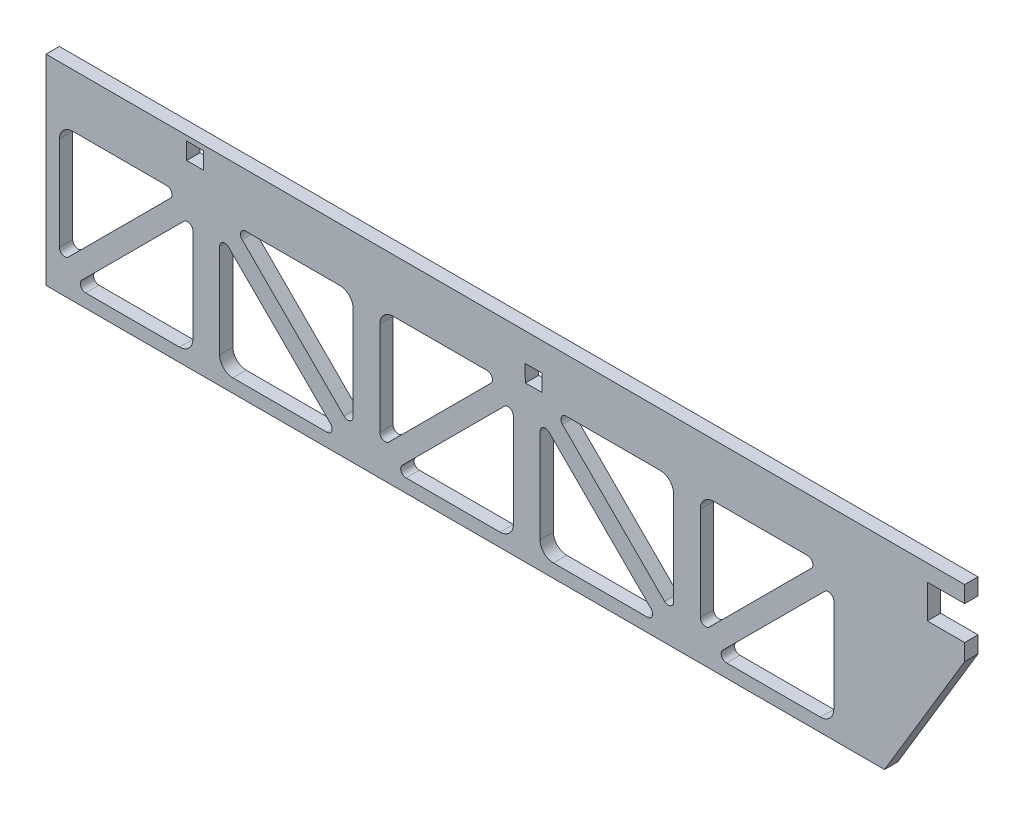
SolidWorks part; units mm, degrees
ref_plane "Front Plane" through (0, 0, 0) normal (0, 0, 1) x (1, 0, 0)
ref_plane "Top Plane" through (0, 0, 0) normal (0, 1, 0) x (1, 0, 0)
ref_plane "Right Plane" through (0, 0, 0) normal (1, 0, 0) x (0, 0, -1)
sketch "Model" plane through (0, 0, 0) normal (0, 0, 1) x (1, 0, 0)
  line L0 (74.8917, 92.9005) -> (74.8917, 84.8995)
  line L1 (74.8917, 84.8995) -> (66.8907, 84.8995)
  line L2 (66.8907, 84.8995) -> (66.8907, 92.9005)
  line L3 (66.8907, 92.9005) -> (74.8917, 92.9005)
  line L4 (235.8537, 81.866) -> (235.9382, 73.8654)
  line L5 (235.9382, 73.8654) -> (227.9376, 73.7809)
  line L6 (227.9376, 73.7809) -> (227.8532, 81.7815)
  line L7 (227.8532, 81.7815) -> (235.8537, 81.866)
  line L8 (171.2321, 6.35) -> (215.9, 6.35)
  line L9 (217.9139, 59.1639) -> (169.4361, 10.6861)
  line L10 (222.25, 57.3679) -> (222.25, 12.7)
  line L11 (234.95, 57.3679) -> (234.95, 12.7)
  line L12 (239.2861, 59.1639) -> (287.7639, 10.6861)
  line L13 (241.3, 6.35) -> (285.9679, 6.35)
  line L14 (294.1139, 17.0361) -> (245.6361, 65.5139)
  line L15 (247.4321, 69.85) -> (292.1, 69.85)
  line L16 (298.45, 63.5) -> (298.45, 18.8321)
  line L17 (323.6321, 6.35) -> (368.3, 6.35)
  line L18 (370.3139, 59.1639) -> (321.8361, 10.6861)
  line L19 (374.65, 57.3679) -> (374.65, 12.7)
  line L20 (18.8321, 6.35) -> (63.5, 6.35)
  line L21 (17.0361, 10.6861) -> (65.5139, 59.1639)
  line L22 (69.85, 57.3679) -> (69.85, 12.7)
  line L23 (82.55, 57.3679) -> (82.55, 12.7)
  line L24 (86.8861, 59.1639) -> (135.3639, 10.6861)
  line L25 (88.9, 6.35) -> (133.5679, 6.35)
  line L26 (93.2361, 65.5139) -> (141.7139, 17.0361)
  line L27 (95.0321, 69.85) -> (139.7, 69.85)
  line L28 (146.05, 63.5) -> (146.05, 18.8321)
  line L29 (163.0861, 17.0361) -> (211.5639, 65.5139)
  line L30 (158.75, 63.5) -> (158.75, 18.8321)
  line L31 (165.1, 69.85) -> (209.7679, 69.85)
  line L32 (315.4861, 17.0361) -> (363.9639, 65.5139)
  line L33 (311.15, 63.5) -> (311.15, 18.8321)
  line L34 (317.5, 69.85) -> (362.1679, 69.85)
  line L35 (419.1, 87.376) -> (419.1, 71.374)
  line L36 (436.88, 87.376) -> (419.1, 87.376)
  line L37 (436.88, 87.376) -> (436.88, 95.25)
  line L38 (0, 95.25) -> (436.88, 95.25)
  line L39 (0, 0) -> (0, 95.25)
  line L40 (0, 0) -> (398.78, 0)
  line L41 (436.88, 63.5) -> (398.78, 0)
  line L42 (436.88, 63.5) -> (436.88, 71.374)
  line L43 (419.1, 71.374) -> (436.88, 71.374)
  line L44 (6.35, 63.5) -> (6.35, 18.8321)
  line L45 (12.7, 69.85) -> (57.3679, 69.85)
  line L46 (59.1639, 65.5139) -> (10.6861, 17.0361)
  arc A0 (215.9, 6.35) -> (222.25, 12.7) centre (215.9, 12.7) ccw
  arc A1 (169.4361, 10.6861) -> (171.2321, 6.35) centre (171.2321, 8.89) ccw
  arc A2 (222.25, 57.3679) -> (217.9139, 59.1639) centre (219.71, 57.3679) ccw
  arc A3 (239.2861, 59.1639) -> (234.95, 57.3679) centre (237.49, 57.3679) ccw
  arc A4 (285.9679, 6.35) -> (287.7639, 10.6861) centre (285.9679, 8.89) ccw
  arc A5 (234.95, 12.7) -> (241.3, 6.35) centre (241.3, 12.7) ccw
  arc A6 (247.4321, 69.85) -> (245.6361, 65.5139) centre (247.4321, 67.31) ccw
  arc A7 (298.45, 63.5) -> (292.1, 69.85) centre (292.1, 63.5) ccw
  arc A8 (294.1139, 17.0361) -> (298.45, 18.8321) centre (295.91, 18.8321) ccw
  arc A9 (321.8361, 10.6861) -> (323.6321, 6.35) centre (323.6321, 8.89) ccw
  arc A10 (374.65, 57.3679) -> (370.3139, 59.1639) centre (372.11, 57.3679) ccw
  arc A11 (368.3, 6.35) -> (374.65, 12.7) centre (368.3, 12.7) ccw
  arc A12 (63.5, 6.35) -> (69.85, 12.7) centre (63.5, 12.7) ccw
  arc A13 (17.0361, 10.6861) -> (18.8321, 6.35) centre (18.8321, 8.89) ccw
  arc A14 (69.85, 57.3679) -> (65.5139, 59.1639) centre (67.31, 57.3679) ccw
  arc A15 (86.8861, 59.1639) -> (82.55, 57.3679) centre (85.09, 57.3679) ccw
  arc A16 (133.5679, 6.35) -> (135.3639, 10.6861) centre (133.5679, 8.89) ccw
  arc A17 (82.55, 12.7) -> (88.9, 6.35) centre (88.9, 12.7) ccw
  arc A18 (95.0321, 69.85) -> (93.2361, 65.5139) centre (95.0321, 67.31) ccw
  arc A19 (146.05, 63.5) -> (139.7, 69.85) centre (139.7, 63.5) ccw
  arc A20 (141.7139, 17.0361) -> (146.05, 18.8321) centre (143.51, 18.8321) ccw
  arc A21 (158.75, 18.8321) -> (163.0861, 17.0361) centre (161.29, 18.8321) ccw
  arc A22 (165.1, 69.85) -> (158.75, 63.5) centre (165.1, 63.5) ccw
  arc A23 (211.5639, 65.5139) -> (209.7679, 69.85) centre (209.7679, 67.31) ccw
  arc A24 (363.9639, 65.5139) -> (362.1679, 69.85) centre (362.1679, 67.31) ccw
  arc A25 (311.15, 18.8321) -> (315.4861, 17.0361) centre (313.69, 18.8321) ccw
  arc A26 (317.5, 69.85) -> (311.15, 63.5) centre (317.5, 63.5) ccw
  arc A27 (6.35, 18.8321) -> (10.6861, 17.0361) centre (8.89, 18.8321) ccw
  arc A28 (12.7, 69.85) -> (6.35, 63.5) centre (12.7, 63.5) ccw
  arc A29 (59.1639, 65.5139) -> (57.3679, 69.85) centre (57.3679, 67.31) ccw
  dimension "D1" = 95.25
extrude "Boss-Extrude2" add sketch "Model" along normal blind 6.35
